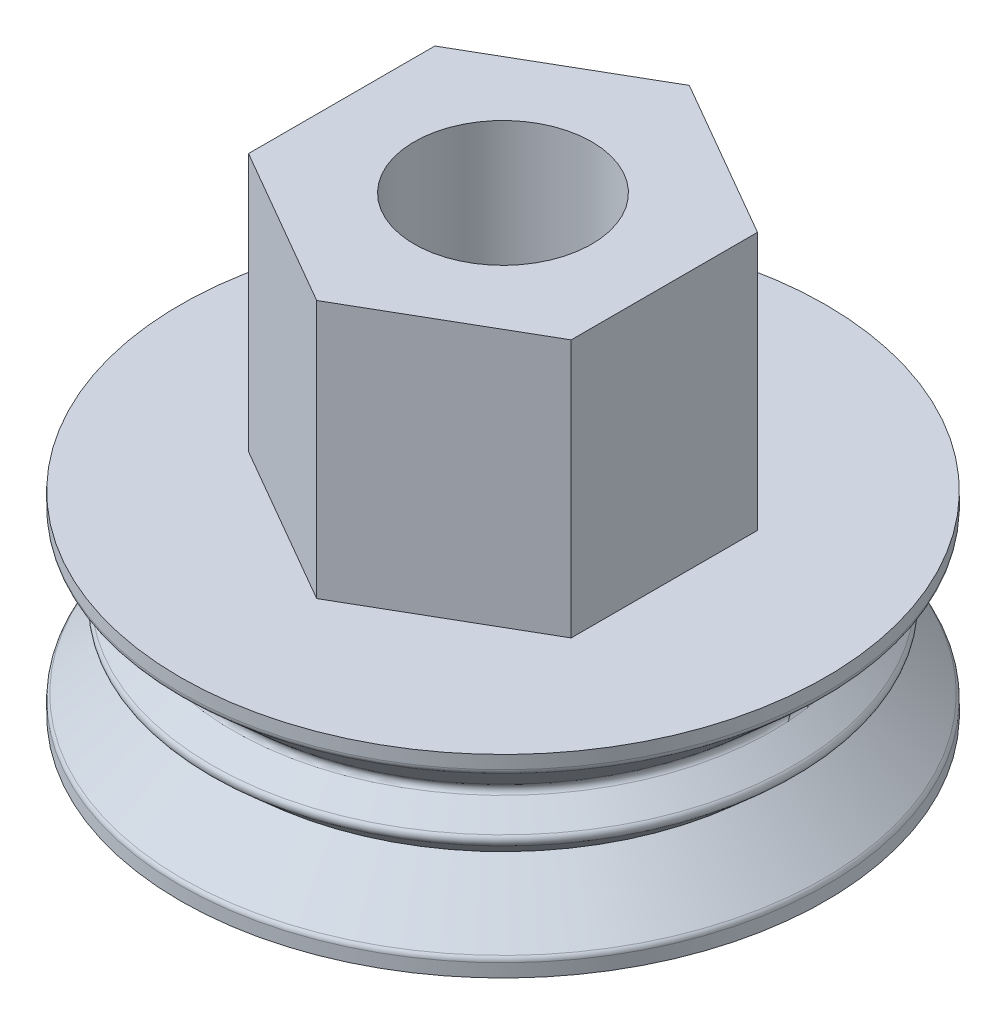
SolidWorks part; units mm, degrees
material "ABS"
ref_plane "Front Plane" through (0, 0, 0) normal (0, 0, 1) x (1, 0, 0)
ref_plane "Top Plane" through (0, 0, 0) normal (0, 1, 0) x (1, 0, 0)
ref_plane "Right Plane" through (0, 0, 0) normal (1, 0, 0) x (0, 0, -1)
sketch "Sketch1" plane through (0, 0, 0) normal (0, 1, 0) x (1, 0, 0)
  line L1 (0, 7.3323) -> (-6.35, 3.6662)
  line L2 (-6.35, 3.6662) -> (-6.35, -3.6662)
  line L3 (-6.35, -3.6662) -> (0, -7.3323)
  line L4 (0, -7.3323) -> (6.35, -3.6662)
  line L5 (6.35, -3.6662) -> (6.35, 3.6662)
  line L6 (6.35, 3.6662) -> (0, 7.3323)
  circle A0 centre (0, 0) radius 6.35 construction
  dimension "D1" = 12.7
extrude "Boss-Extrude1" add sketch "Sketch1" along normal blind 10.16
sketch "Sketch3" plane through (0, 0, 0) normal (0, 0, 1) x (1, 0, 0)
  line L0 (0, 0) -> (-12.7, 0)
  line L1 (-12.7, 0) -> (-12.7, -0.635)
  line L2 (-12.7, -0.635) -> (-10.3991, -2.6808)
  line L3 (-12.7, -7.62) -> (0, -7.62)
  line L4 (0, -7.62) -> (0, 0)
  line L5 (-10.3991, -2.6808) -> (-11.6691, -3.81)
  line L6 (-11.6691, -3.81) -> (-10.3991, -4.9392)
  line L7 (-10.3991, -4.9392) -> (-12.7, -6.985)
  line L8 (-12.7, -6.985) -> (-12.7, -7.62)
  dimension "D1" = 7.62
  dimension "D3" = 6.35
  dimension "D2" = 12.7
  dimension "D4" = 1.27
revolve "Revolve1" add sketch "Sketch3" angle 360 about L4
fillet "Fillet1" radius 0.254 4 edges at (0, -3.81, -11.6691) (0, -0.635, -12.7) (0, -6.985, -12.7) (0, -2.6808, -10.3991)
sketch "Sketch4" plane through (0, -7.62, 0) normal (0, -1, 0) x (1, 0, 0)
  circle A0 centre (0, 0) radius 3.4925
  dimension "D1" = 6.985
extrude "Cut-Extrude1" cut sketch "Sketch4" against normal through all
